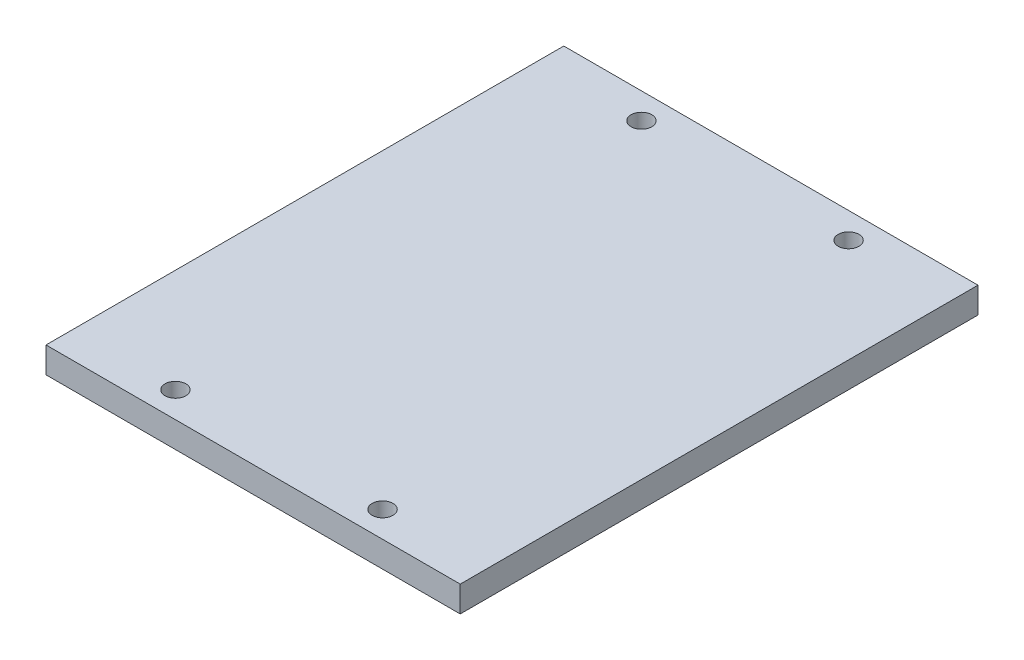
SolidWorks part; units mm, degrees
material "6061 Alloy"
ref_plane "Front" through (0, 0, 0) normal (0, 0, 1) x (1, 0, 0)
ref_plane "Top" through (0, 0, 0) normal (0, 1, 0) x (1, 0, 0)
ref_plane "Right" through (0, 0, 0) normal (1, 0, 0) x (0, 0, -1)
sketch "Sketch1" plane through (0, 0, 0) normal (0, 1, 0) x (1, 0, 0)
  line L1 (-50.8, -63.5) -> (50.8, -63.5)
  line L2 (-50.8, -63.5) -> (-50.8, 63.5)
  line L3 (-50.8, 63.5) -> (50.8, 63.5)
  line L4 (50.8, -63.5) -> (50.8, 63.5)
  line L5 (-50.8, -63.5) -> (50.8, 63.5) construction
  line L6 (-50.8, 63.5) -> (50.8, -63.5) construction
  point P0 (0, 0)
  dimension "D1" = 101.6
  dimension "D2" = 127
extrude "Boss-Extrude1" add sketch "Sketch1" along normal blind 6.35
sketch "Sketch3" plane through (0, 6.35, 0) normal (0, 1, 0) x (1, 0, 0)
  line L0 (50.8, 63.5) -> (-50.8, 63.5) construction
  line L1 (-50.8, 63.5) -> (-50.8, -63.5) construction
  line L2 (0, 63.5) -> (0, -63.5) construction
  line L3 (-50.8, -63.5) -> (50.8, -63.5) construction
  line L4 (-50.8, 0) -> (50.8, 0) construction
  line L5 (50.8, -63.5) -> (50.8, 63.5) construction
  circle A0 centre (-25.4, 57.15) radius 2.5527
  circle A4 centre (-25.4, -57.15) radius 2.5527
  circle A5 centre (25.4, -57.15) radius 2.5527
  circle A6 centre (25.4, 57.15) radius 2.5527
  dimension "D3" = 5.1054
  dimension "D1" = 6.35
  dimension "D2" = 25.4
extrude "Cut-Extrude2" cut sketch "Sketch3" against normal blind 9.525
